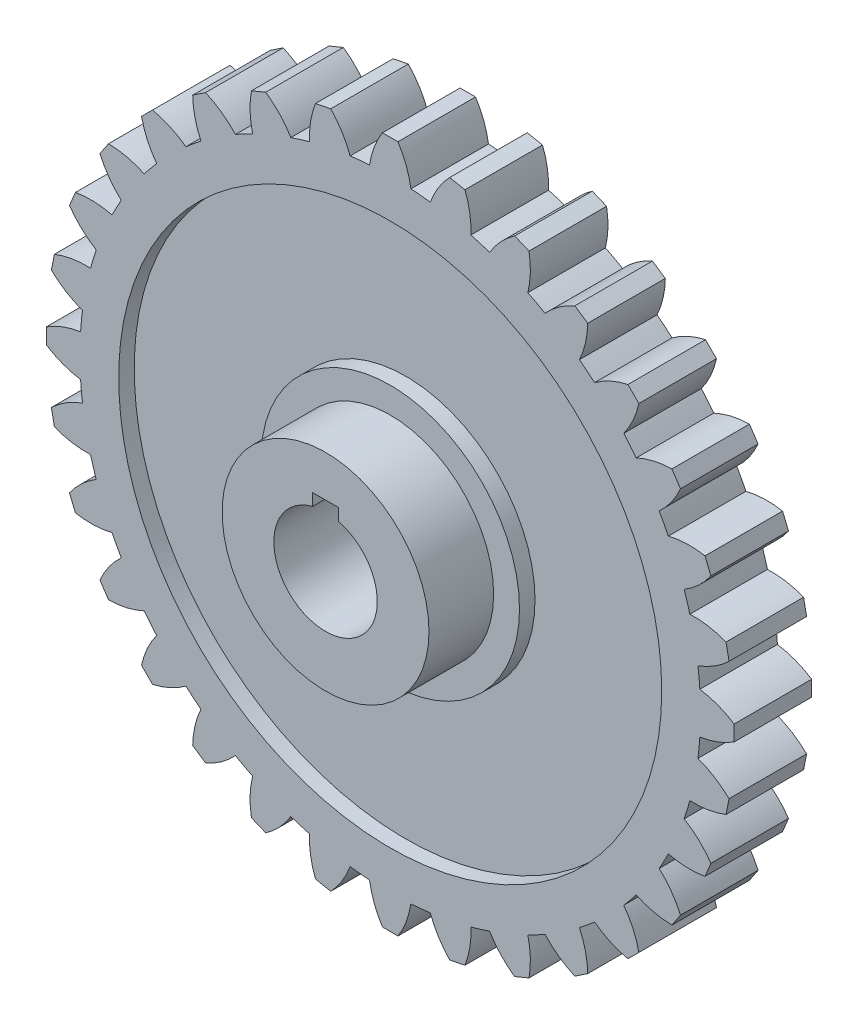
SolidWorks part; units mm, degrees
ref_plane "Front Plane" through (0, 0, 0) normal (0, 0, 1) x (1, 0, 0)
ref_plane "Top Plane" through (0, 0, 0) normal (0, 1, 0) x (1, 0, 0)
ref_plane "Right Plane" through (0, 0, 0) normal (1, 0, 0) x (0, 0, -1)
sketch "Sketch1" plane through (0, 0, 0) normal (0, 0, 1) x (1, 0, 0)
  circle A0 centre (0, 0) radius 60
  dimension "D1" = 120
extrude "Boss-Extrude1" add sketch "Sketch1" against normal mid plane 15
sketch "Sketch2" plane through (0, 0, 7.5) normal (0, 0, 1) x (1, 0, 0)
  line L0 (0, 0) -> (0, 66.5) construction
  line L1 (-1.5, 66.5) -> (1.5, 66.5)
  line L2 (11.753, 60) -> (-13.2963, 60) construction
  arc A0 (-1.5, 66.5) -> (-4, 59.8665) centre (12.8082, 57.3198) ccw
  circle A1 centre (0, 0) radius 60 construction
  arc A2 (1.5, 66.5) -> (4, 59.8665) centre (-12.8082, 57.3198) cw
  arc A3 (-4, 59.8665) -> (4, 59.8665) centre (0, 0) cw
  circle A4 centre (0, 0) radius 60
  arc A5 (-4, 59.8665) -> (4, 59.8665) centre (0, 0) ccw
  point P6 (0, 66.5)
  circle M5 centre (0, 0) radius 60
  dimension "D1" = 6.5
  dimension "D3" = 8
  dimension "D2" = 3
  dimension "D4" = 0
extrude "Boss-Extrude3" add sketch "Sketch2" against normal through all contours A2 L1 A0 M5
pattern_circular "CirPattern1" count 32 over 360 about axis through (0, 0, 0) along (0, 0, 1) of "Boss-Extrude3"
sketch "Sketch4" plane through (0, 0, 0) normal (0, 0, 1) x (1, 0, 0)
  circle A0 centre (0, 0) radius 20
  dimension "D1" = 40
extrude "Boss-Extrude4" add sketch "Sketch4" along normal mid plane 40
sketch "Sketch5" plane through (0, 0, 20) normal (0, 0, 1) x (1, 0, 0)
  line L0 (0, 0) -> (0, 12) construction
  line L1 (-2.5, 12) -> (2.5, 12)
  line L2 (-2.5, 12) -> (-2.5, 9.6825)
  line L3 (2.5, 12) -> (2.5, 9.6825)
  arc A0 (-2.5, 9.6825) -> (2.5, 9.6825) centre (0, 0) ccw
  point P7 (0, 12)
  dimension "D1" = 20
  dimension "D2" = 12
  dimension "D3" = 5
extrude "Cut-Extrude1" cut sketch "Sketch5" against normal through all both and the other way through all
sketch "Sketch6" plane through (0, 0, 0) normal (0, 0, 1) x (1, 0, 0)
  circle A1 centre (0, 0) radius 52.5
  circle A2 centre (0, 0) radius 25
  circle A3 centre (0, 0) radius 25
  dimension "D2" = 105
  dimension "D1" = 5
extrude "Cut-Extrude2" cut sketch "Sketch6" against normal blind 3 from surface at 7.5 starting at face at (20, 0, 7.5)
sketch "Sketch7" plane through (0, 0, -7.5) normal (0, 0, -1) x (-1, 0, 0)
  circle A97 centre (0, 0) radius 52.5
  circle A98 centre (0, 0) radius 25
  circle A99 centre (0, 0) radius 25
  circle A192 centre (0, 0) radius 55
  circle A193 centre (0, 0) radius 55
  dimension "D3" = 105
  dimension "D1" = 5
  dimension "D2" = 5
extrude "Cut-Extrude3" cut sketch "Sketch7" against normal blind 3 from surface contours A97 A99
